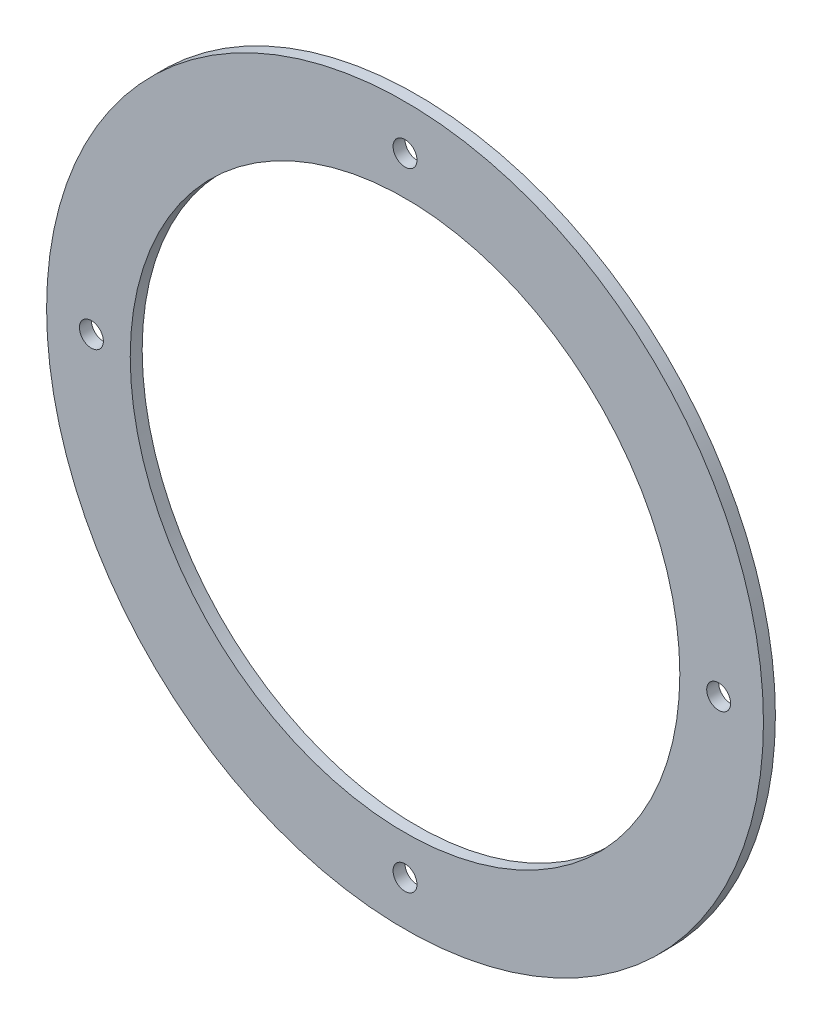
SolidWorks part; units mm, degrees
material "Thornel Mat VMA"
ref_plane "前视基准面" through (0, 0, 0) normal (0, 0, 1) x (1, 0, 0)
ref_plane "上视基准面" through (0, 0, 0) normal (0, 1, 0) x (1, 0, 0)
ref_plane "右视基准面" through (0, 0, 0) normal (1, 0, 0) x (0, 0, -1)
sketch "草图1" plane through (0, 0, 0) normal (0, 0, 1) x (1, 0, 0)
  circle A0 centre (-52.5, 0) radius 2
  circle A1 centre (0, 52.5) radius 2
  circle A2 centre (52.5, 0) radius 2
  circle A3 centre (0, -52.5) radius 2
  circle A4 centre (0, 0) radius 46
  circle A5 centre (0, 0) radius 75
  point P12 (0, 0)
  dimension "D1" = 2
  dimension "D2" = 52.5
  dimension "D4" = 46
  dimension "D5" = 75
  dimension "D3" = 4
extrude "凸台-拉伸1" add sketch "草图1" along normal blind 2
sketch "草图2" plane through (0, 0, 2) normal (0, 0, 1) x (1, 0, 0)
  circle A0 centre (0, 69) radius 1.5
  circle A1 centre (69, 0) radius 1.5
  circle A2 centre (0, -69) radius 1.5
  circle A3 centre (-69, 0) radius 1.5
  point P12 (0, 0)
  dimension "D1" = 1.5
  dimension "D2" = 69
  dimension "D3" = 4
extrude "切除-拉伸1" cut sketch "草图2" against normal blind 2
sketch "草图4" plane through (0, 0, 2) normal (0, 0, 1) x (1, 0, 0)
  circle A0 centre (0, 0) radius 60
  dimension "D1" = 60
extrude "切除-拉伸2" cut sketch "草图4" against normal blind 10 flip side to cut
